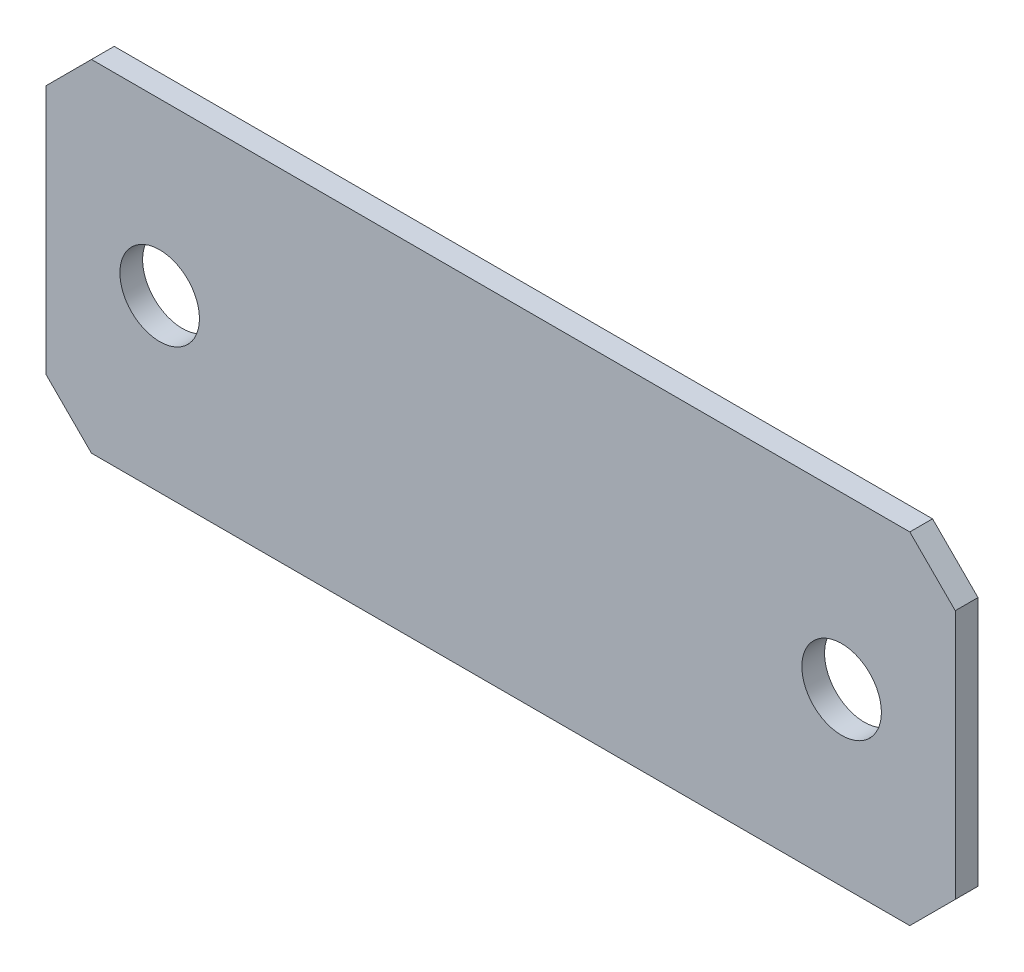
SolidWorks part; units mm, degrees
ref_plane "Ebene vorne" through (0, 0, 0) normal (0, 0, 1) x (1, 0, 0)
ref_plane "Ebene oben" through (0, 0, 0) normal (0, 1, 0) x (1, 0, 0)
ref_plane "Ebene rechts" through (0, 0, 0) normal (1, 0, 0) x (0, 0, -1)
sketch "Skizze1" plane through (0, 0, 0) normal (0, 0, 1) x (1, 0, 0)
  line L0 (-15, 0) -> (15, 0) construction
  line L1 (20, -7.5) -> (-20, -7.5)
  line L2 (20, -7.5) -> (20, 7.5)
  line L3 (20, 7.5) -> (-20, 7.5)
  line L4 (-20, -7.5) -> (-20, 7.5)
  line L5 (20, -7.5) -> (-20, 7.5) construction
  line L6 (20, 7.5) -> (-20, -7.5) construction
  circle A0 centre (-15, 0) radius 1.75
  circle A1 centre (15, 0) radius 1.75
  point P0 (0, 0)
  dimension "D4" = 3.5
  dimension "D1" = 15
  dimension "D2" = 40
  dimension "D3" = 30
extrude "Aufsatz-Linear austragen1" add sketch "Skizze1" along normal blind 1
chamfer "Fase1" distance 2 angle 45 4 edges at (-20, 7.5, 0.5) (-20, -7.5, 0.5) (20, -7.5, 0.5) (20, 7.5, 0.5)
